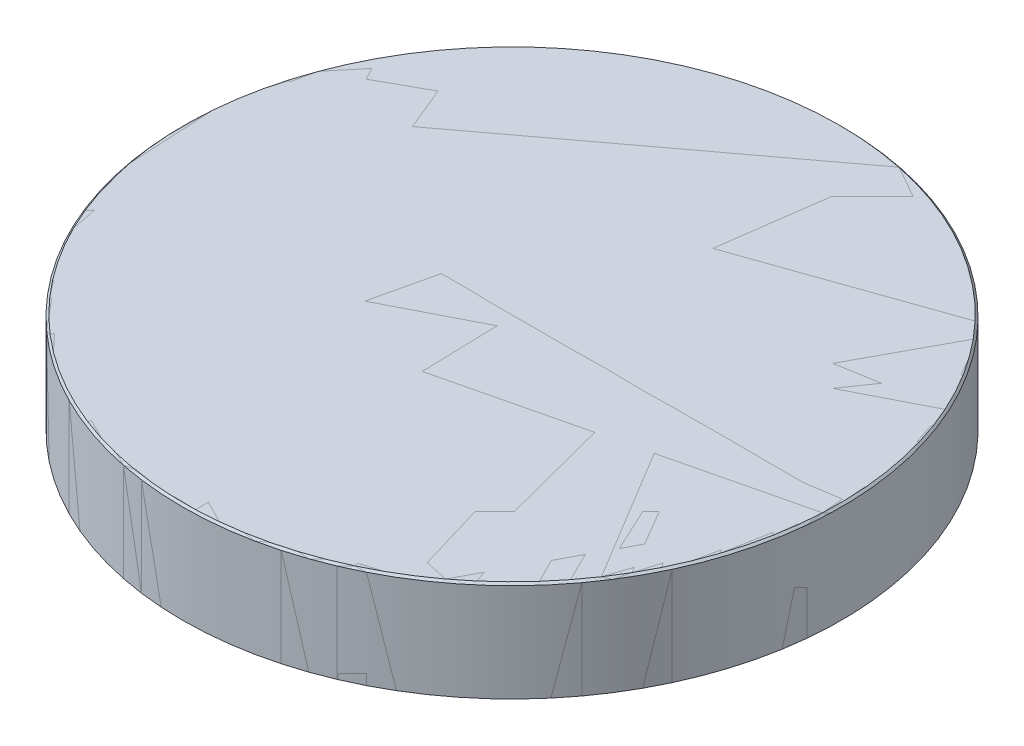
SolidWorks part; units mm, degrees
material "Brass"
ref_plane "Front Plane" through (0, 0, 0) normal (0, 0, 1) x (1, 0, 0)
ref_plane "Top Plane" through (0, 0, 0) normal (0, 1, 0) x (1, 0, 0)
ref_plane "Right Plane" through (0, 0, 0) normal (1, 0, 0) x (0, 0, -1)
sketch "Sketch3" plane through (0, 0, 0) normal (0, 1, 0) x (1, 0, 0)
  circle A0 centre (0, 0) radius 4.1783
  dimension "D1" = 8.3566
extrude "Boss-Extrude1" add sketch "Sketch3" along normal blind 1.27
chamfer "Chamfer1" distance 0.0254 angle 45 1 edges at (0, 1.27, 4.1783)
sketch "Text" plane through (0, 1.27, 0) normal (0, 1, 0) x (1, 0, 0)
  line L0 (-4.0021, 0) -> (4.0021, 0) construction
  text T0 "SWIRL INJECTOR V1" font "GDT" height 0.508
  point P4 (0, 0)
extrude "Cut-Extrude2" cut sketch "Text" against normal blind 0.0254
ref_plane "Plane1" through (0, 1.27, 0) normal (1, 0, 0) x (0, 1, 0)
sketch "Spun Profile Sketch1" plane through (0, 1.27, 0) normal (1, 0, 0) x (0, 1, 0)
  line L0 (-1.27, 0) -> (0, 0)
  line L1 (0, 0) -> (0, 4.1529)
  line L2 (0, 4.1529) -> (-0.0254, 4.1783)
  line L3 (-0.0254, 4.1783) -> (-1.27, 4.1783)
  line L4 (-1.27, 4.1783) -> (-1.27, 0)
  line L5 (0, 0) -> (1000, 0) construction
revolve "Revolve" add sketch "Spun Profile Sketch1" angle 360 about L5
